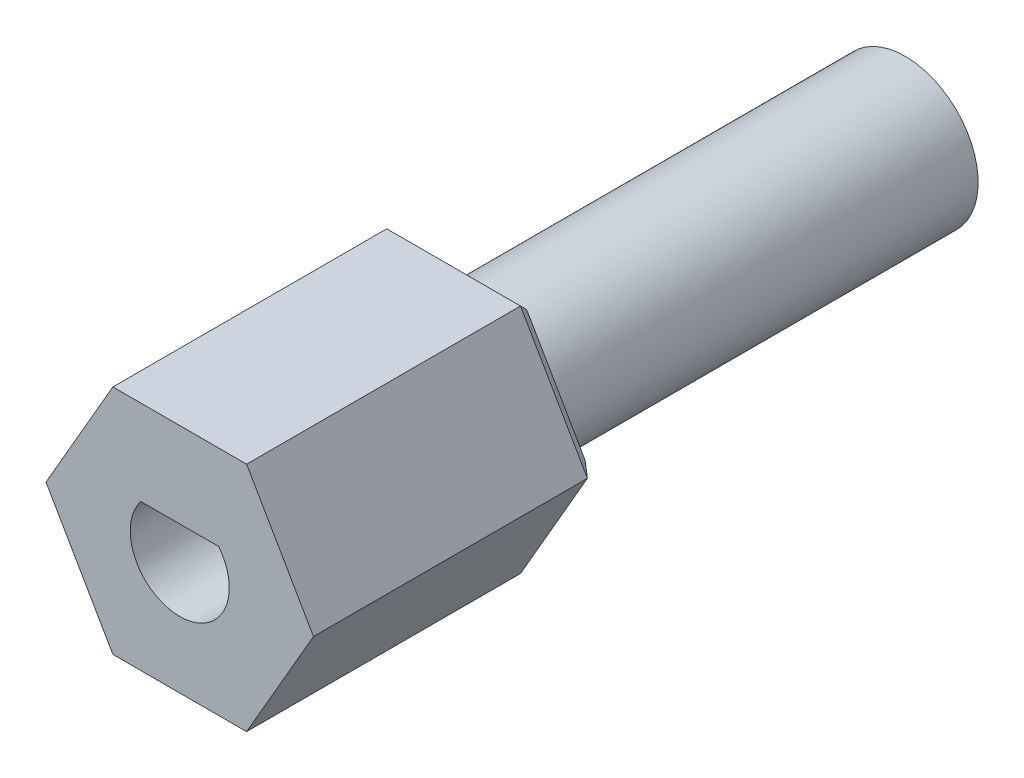
SolidWorks part; units mm, degrees
ref_plane "Alzado" through (0, 0, 0) normal (0, 0, 1) x (1, 0, 0)
ref_plane "Planta" through (0, 0, 0) normal (0, 1, 0) x (1, 0, 0)
ref_plane "Vista lateral" through (0, 0, 0) normal (1, 0, 0) x (0, 0, -1)
sketch "Croquis1" plane through (0, 0, 0) normal (0, 0, 1) x (1, 0, 0)
  line L1 (4.5899, 0) -> (2.295, 3.975)
  line L2 (2.295, 3.975) -> (-2.295, 3.975)
  line L3 (-2.295, 3.975) -> (-4.5899, 0)
  line L4 (-4.5899, 0) -> (-2.295, -3.975)
  line L5 (-2.295, -3.975) -> (2.295, -3.975)
  line L6 (2.295, -3.975) -> (4.5899, 0)
  circle A0 centre (0, 0) radius 3.975 construction
  dimension "D1" = 7.95
extrude "Saliente-Extruir1" add sketch "Croquis1" along normal blind 9.9
sketch "Croquis2" plane through (0, 0, 9.9) normal (0, 0, 1) x (1, 0, 0)
  line L0 (0, 0) -> (50000, 0) construction
  line L1 (0, 0) -> (0, 50000) construction
  line L14 (-1.337, 1.05) -> (1.337, 1.05)
  arc A1 (-1.337, 1.05) -> (1.337, 1.05) centre (0, 0) ccw
  dimension "D1" = 1.05
  dimension "D3" = 3.4
extrude "Cortar-Extruir1" cut sketch "Croquis2" against normal blind 8
sketch "Croquis3" plane through (0, 0, 0) normal (0, 0, -1) x (-1, 0, 0)
  circle A0 centre (0, 0) radius 2.5
  dimension "D1" = 5
extrude "Saliente-Extruir2" add sketch "Croquis3" along normal blind 15
sketch "Croquis4" plane through (0, 0, -15) normal (0, 0, -1) x (-1, 0, 0)
  circle A0 centre (0, 0) radius 1.45
  dimension "D1" = 2.9
extrude "Cortar-Extruir2" cut sketch "Croquis4" against normal blind 14
chamfer "Chaflán1" distance 0.5 angle 45 6 edges at (0, -3.975, 0) (-3.4425, -1.9875, 0) (-3.4425, 1.9875, 0) (0, 3.975, 0) (3.4425, 1.9875, 0) (3.4425, -1.9875, 0)
chamfer "Chaflán2" distance 0.5 angle 45 1 edges at (-1.45, 0, -15)
